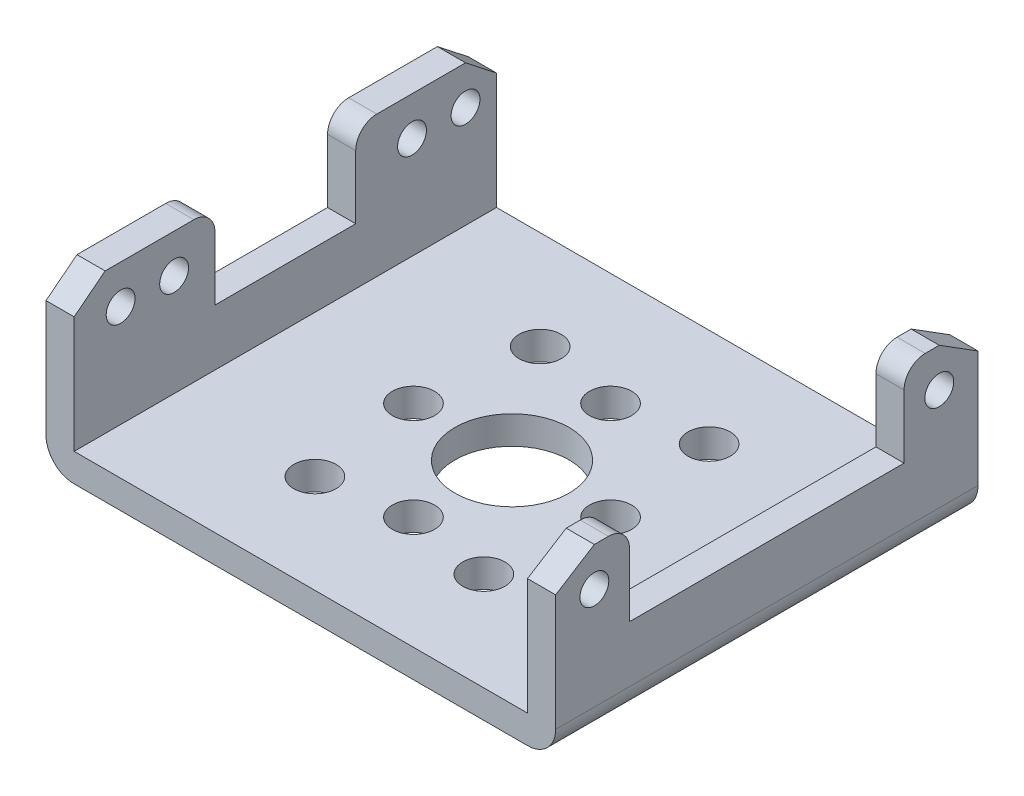
SolidWorks part; units mm, degrees
ref_plane "前视基准面" through (0, 0, 0) normal (0, 0, 1) x (1, 0, 0)
ref_plane "上视基准面" through (0, 0, 0) normal (0, 1, 0) x (1, 0, 0)
ref_plane "右视基准面" through (0, 0, 0) normal (1, 0, 0) x (0, 0, -1)
sketch "草图1" plane through (0, 0, 0) normal (0, 0, 1) x (1, 0, 0)
  line L0 (-16.1, 0) -> (16.1, 0)
  line L1 (0, 0) -> (0, -2) construction
  line L2 (-16.1, -2) -> (16.1, -2)
  line L3 (18.1, 0) -> (18.1, 10)
  line L4 (18.1, 10) -> (16.1, 10)
  line L5 (16.1, 10) -> (16.1, 0)
  line L6 (-16.1, 0) -> (-16.1, 10)
  line L7 (-16.1, 10) -> (-18.1, 10)
  line L8 (-18.1, 10) -> (-18.1, 0)
  arc A0 (16.1, -2) -> (18.1, 0) centre (16.1, 0) ccw
  arc A1 (-16.1, -2) -> (-18.1, 0) centre (-16.1, 0) cw
  point P4 (0, 0)
  point P8 (0, -2)
  point P15 (18.1, -2)
  dimension "D5" = 2
  dimension "D1" = 2
  dimension "D2" = 18.1
  dimension "D3" = 12
  dimension "D4" = 2
extrude "凸台-拉伸1" add sketch "草图1" along normal blind 30
sketch "草图2" plane through (18.1, 0, 0) normal (1, 0, 0) x (0, 0, -1)
  line L0 (-30, -2) -> (-30, 4)
  line L1 (-30, 0) -> (-30, 10) construction
  line L2 (-15, -2) -> (-15, 10) construction
  line L3 (-30, -2) -> (0, -2) construction
  line L4 (-30, 10) -> (0, 10) construction
  line L5 (0, -2) -> (0, 7.25) construction
  line L6 (0, 0) -> (0, 10) construction
  line L7 (0, 7.25) -> (-2.75, 7.25) construction
  line L8 (-2.75, 10) -> (0, 8.275)
  line L9 (-2.75, 10) -> (0, 10)
  line L10 (0, 10) -> (0, 8.275)
  line L11 (-24.75, 4) -> (-5.25, 4)
  line L12 (-5.25, 4) -> (-5.25, 8.5)
  line L13 (-3.75, 10) -> (-2.75, 10)
  line L14 (-3.75, 10) -> (-26.25, 10)
  line L15 (-30, 10) -> (-30, 8.275)
  line L16 (-27.25, 10) -> (-30, 10)
  line L17 (-27.25, 10) -> (-30, 8.275)
  line L18 (-24.75, 4) -> (-24.75, 8.5)
  circle A0 centre (-2.75, 7.25) radius 1.025
  arc A1 (-5.25, 8.5) -> (-3.75, 10) centre (-3.75, 8.5) cw
  circle A2 centre (-27.25, 7.25) radius 1.025
  arc A3 (-24.75, 8.5) -> (-26.25, 10) centre (-26.25, 8.5) ccw
  point P27 (-5.25, 10)
  point P37 (-15, 4)
  line M10 (0, 0) -> (0, 10)
  line M11 (0, 10) -> (-30, 10)
  line M12 (-30, 10) -> (-30, 0)
  dimension "D4" = 2.05
  dimension "D6" = 1.5
  dimension "D1" = 6
  dimension "D2" = 9.25
  dimension "D3" = 2.75
  dimension "D5" = 9.75
extrude "切除-拉伸1" cut sketch "草图2" against normal blind 4 contours L17 M11 M12 | A3 L18 L11 L12 A1 M11 | A2 | A0 | L8 M11 M10
sketch "草图3" plane through (-18.1, 0, 0) normal (-1, 0, 0) x (0, 0, 1)
  line L0 (-1.2286, 10) -> (-1.2286, 7.25) construction
  line L1 (-1.2286, 7.25) -> (33.5558, 7.25) construction
  line L2 (15, -2) -> (15, 10) construction
  line L3 (15, 7.25) -> (6, 7.25) construction
  line L4 (30, -2) -> (0, -2) construction
  line L5 (30, 10) -> (0, 10) construction
  line L6 (10, 4) -> (20, 4)
  line L7 (15, 7.25) -> (2.2, 7.25) construction
  line L8 (2.2, 10) -> (0, 8.275)
  line L9 (0, 8.275) -> (0, 10)
  line L10 (0, 10) -> (2.2, 10)
  line L11 (15, 7.25) -> (22.9, 7.25) construction
  line L12 (15, 7.25) -> (26.7, 7.25) construction
  line L13 (10, 4) -> (10, 8.5)
  line L15 (20, 8.5) -> (20, 4)
  line L16 (30, 10) -> (27.8, 10)
  line L17 (30, 8.275) -> (30, 10)
  line L18 (27.8, 10) -> (30, 8.275)
  line L19 (8.5, 10) -> (2.2, 10)
  line L20 (21.5, 10) -> (27.8, 10)
  line L21 (8.5, 10) -> (21.5, 10)
  circle A0 centre (2.2, 7.25) radius 1.025
  circle A1 centre (6, 7.25) radius 1.025
  circle A2 centre (22.9, 7.25) radius 1.025
  circle A3 centre (26.7, 7.25) radius 1.025
  arc A4 (21.5, 10) -> (20, 8.5) centre (21.5, 8.5) ccw
  arc A5 (10, 8.5) -> (8.5, 10) centre (8.5, 8.5) ccw
  point P12 (15, 4)
  point P33 (20, 10)
  point P36 (10, 10)
  line M9 (0, 10) -> (0, 0)
  line M11 (30, 0) -> (30, 10)
  line M12 (30, 10) -> (0, 10)
  dimension "D3" = 2.05
  dimension "D5" = 2.05
  dimension "D7" = 2.05
  dimension "D9" = 2.05
  dimension "D10" = 1.5
  dimension "D1" = 2.75
  dimension "D2" = 12.8
  dimension "D4" = 9
  dimension "D6" = 7.9
  dimension "D8" = 11.7
extrude "切除-拉伸2" cut sketch "草图3" against normal blind 4 contours L8 M12 M9 | A0 | A1 | A5 L13 L6 L15 A4 M12 | A2 | A3 | L18 M12 M11
sketch "草图4" plane through (0, -2, 0) normal (0, -1, 0) x (1, 0, 0)
  circle A0 centre (0, 15) radius 4.05
  circle A2 centre (7, 15) radius 1.5
  circle A3 centre (0, 8) radius 1.5
  circle A4 centre (-7, 15) radius 1.5
  circle A5 centre (0, 22) radius 1.5
  circle A6 centre (-6, 23.0004) radius 1.5
  circle A7 centre (6, 23.0004) radius 1.5
  circle A8 centre (-6, 7.0004) radius 1.5
  circle A9 centre (6, 7.0004) radius 1.5
  point P14 (0, 25.1595)
  point P17 (-10.1194, 15.0004)
  dimension "D1" = 8.1
  dimension "D3" = 3
  dimension "D4" = 3
  dimension "D5" = 3
  dimension "D6" = 3
  dimension "D7" = 3
  dimension "D8" = 3
  dimension "D9" = 3
  dimension "D10" = 3
extrude "切除-拉伸3" cut sketch "草图4" against normal blind 10
